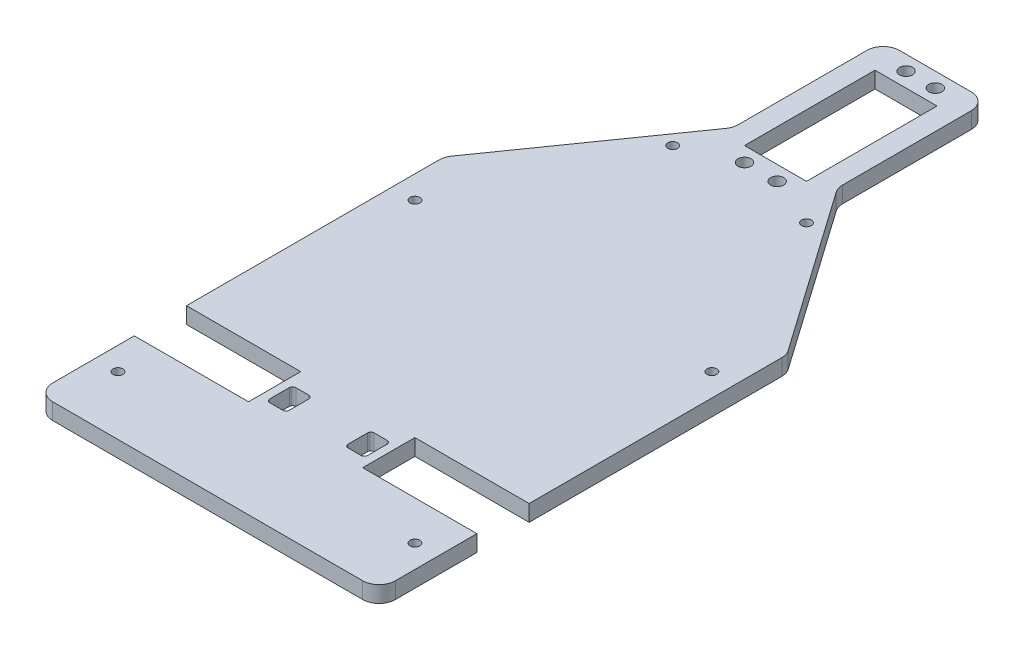
SolidWorks part; units mm, degrees
ref_plane "Front Plane" through (0, 0, 0) normal (0, 0, 1) x (1, 0, 0)
ref_plane "Top Plane" through (0, 0, 0) normal (0, 1, 0) x (1, 0, 0)
ref_plane "Right Plane" through (0, 0, 0) normal (1, 0, 0) x (0, 0, -1)
sketch "Sketch1" plane through (0, 0, 0) normal (0, 1, 0) x (1, 0, 0)
  line L0 (-16, 108) -> (16, 108)
  line L1 (16, 108) -> (16, 62)
  line L2 (16, 62) -> (52.5, 10)
  line L3 (52.5, 10) -> (52.5, -115)
  line L4 (52.5, -115) -> (-52.5, -115)
  line L5 (-52.5, -115) -> (-52.5, 10)
  line L6 (-52.5, 10) -> (-16, 62)
  line L7 (-16, 62) -> (-16, 108)
  dimension "D1" = 52.5
  dimension "D2" = 105
  dimension "D3" = 16
  dimension "D4" = 32
  dimension "D5" = 125
  dimension "D6" = 108
  dimension "D7" = 125
  dimension "D8" = 46
  dimension "D9" = 52
  dimension "D10" = 52
extrude "Boss-Extrude1" add sketch "Sketch1" along normal blind 5
sketch "Sketch2" plane through (0, 5, 0) normal (0, 1, 0) x (1, 0, 0)
  line L5 (-9.5, 59) -> (-9.5, 99)
  line L16 (52.5, 10) -> (52.5, -115) construction
  line L17 (-52.5, -69) -> (-17.5, -69)
  line L18 (-52.5, -115) -> (-52.5, 10) construction
  line L19 (-17.5, -69) -> (-17.5, -85)
  line L20 (-17.5, -85) -> (-52.5, -85)
  line L21 (-52.5, -85) -> (-52.5, -69)
  line L22 (17.5, -85) -> (17.5, -69)
  line L23 (17.5, -85) -> (52.5, -85)
  line L24 (17.5, -69) -> (52.5, -69)
  line L25 (52.5, -69) -> (52.5, -85)
  line L27 (52.5, -115) -> (-52.5, -115) construction
  line L29 (-15, -82) -> (-9, -82)
  line L30 (-9, -82) -> (-9, -74)
  line L31 (-15, -74) -> (-9, -74)
  line L32 (-15, -82) -> (-15, -74)
  line L33 (9, -74) -> (9, -82)
  line L34 (9, -82) -> (15, -82)
  line L35 (15, -82) -> (15, -74)
  line L36 (15, -74) -> (9, -74)
  line L37 (-16, 108) -> (16, 108) construction
  line L38 (-16, 62) -> (-16, 108) construction
  line L40 (-9.5, 99) -> (9.5, 99)
  line L41 (9.5, 99) -> (9.5, 59)
  line L42 (9.5, 59) -> (-9.5, 59)
  circle A0 centre (-4.5, 103.5) radius 2
  circle A1 centre (4.5, 103.5) radius 2
  circle A2 centre (-5, 54.5026) radius 2
  circle A3 centre (5, 54.5026) radius 2
  circle A6 centre (-20.5, 48) radius 1.5
  circle A7 centre (20.5, 48) radius 1.5
  circle A8 centre (45.5, -6) radius 1.5
  circle A9 centre (-45.5, -6) radius 1.5
  circle A10 centre (45.5, -97) radius 1.5
  circle A11 centre (-45.5, -97) radius 1.5
  point P4 (0, 0)
  dimension "D5" = 4
  dimension "D8" = 4
  dimension "D11" = 4
  dimension "D14" = 40
  dimension "D21" = 91
  dimension "D24" = 16
  dimension "D27" = 3
  dimension "D30" = 3
  dimension "D37" = 3
  dimension "D38" = 3
  dimension "D39" = 3
  dimension "D40" = 3
  dimension "D26" = 4
  dimension "D7" = 4.5
  dimension "D9" = 19
  dimension "D10" = 4.5
  dimension "D12" = 6.5
  dimension "D13" = 11
  dimension "D15" = 49
  dimension "D16" = 49
  dimension "D17" = 11
  dimension "D18" = 60
  dimension "D19" = 60
  dimension "D20" = 7
  dimension "D22" = 91
  dimension "D23" = 32
  dimension "D25" = 16
  dimension "D28" = 32
  dimension "D33" = 7
  dimension "D35" = 7
  dimension "D41" = 7
  dimension "D42" = 4.5
  dimension "D44" = 5
  dimension "D45" = 5
  dimension "D49" = 35
  dimension "D50" = 16
  dimension "D51" = 30
  dimension "D52" = 16
  dimension "D53" = 35
  dimension "D54" = 30
  dimension "D55" = 8
  dimension "D56" = 6
  dimension "D57" = 2.5
  dimension "D58" = 5
  dimension "D59" = 8
  dimension "D60" = 6
  dimension "D61" = 2.5
  dimension "D62" = 5
extrude "Cut-Extrude1" cut sketch "Sketch2" against normal blind 7
fillet "Fillet1" radius 5 1 edges at (16, 2.5, -108)
fillet "Fillet2" radius 5 1 edges at (-16, 2.5, -108)
fillet "Fillet3" radius 5 1 edges at (52.5, 2.5, -10)
fillet "Fillet4" radius 5 1 edges at (-52.5, 2.5, -10)
fillet "Fillet5" radius 5 1 edges at (52.5, 2.5, 115)
fillet "Fillet6" radius 5 1 edges at (-52.5, 2.5, 115)
fillet "Fillet8" radius 1 1 edges at (15, 2.5, 74)
fillet "Fillet9" radius 1 7 edges at (-15, 2.5, 82) (-15, 2.5, 74) (-9, 2.5, 82) (-9, 2.5, 74) (9, 2.5, 82) (15, 2.5, 82) (9, 2.5, 74)
fillet "Fillet10" radius 5 2 edges at (-16, 2.5, -62) (16, 2.5, -62)
